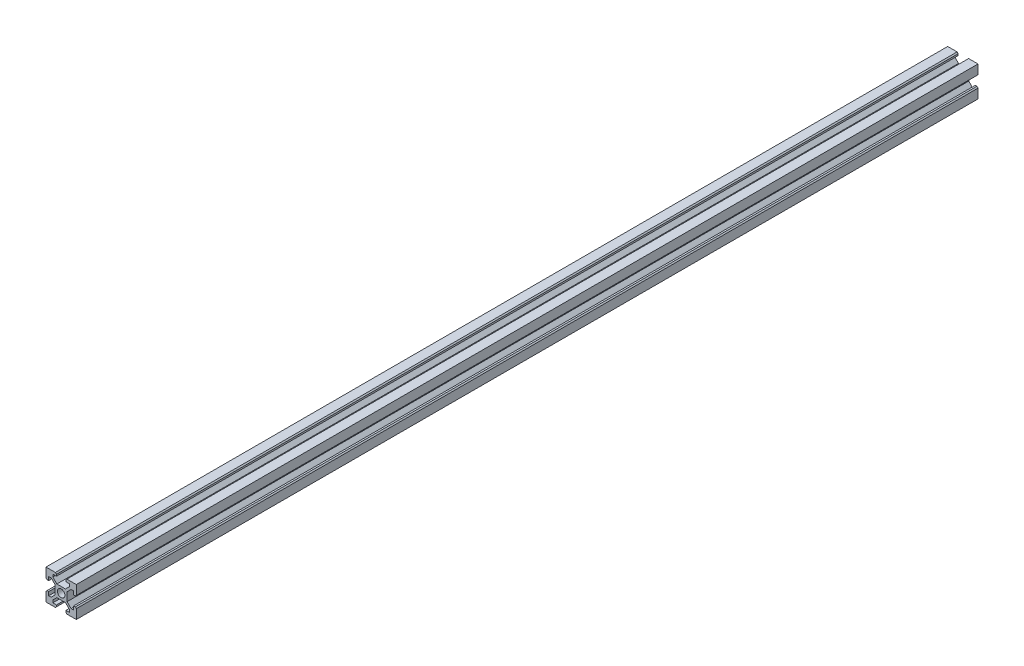
SolidWorks part; units mm, degrees
material "1060 Alloy"
ref_plane "Front Plane" through (0, 0, 0) normal (0, 0, 1) x (1, 0, 0)
ref_plane "Top Plane" through (0, 0, 0) normal (0, 1, 0) x (1, 0, 0)
ref_plane "Right Plane" through (0, 0, 0) normal (1, 0, 0) x (0, 0, -1)
sketch "Sketch1" plane through (0, 0, 0) normal (0, 0, 1) x (1, 0, 0)
  line L0 (3.9, -2.8393) -> (6.5607, -5.5)
  line L1 (-10, 10) -> (10, 10) construction
  line L2 (-10, 10) -> (-10, -10) construction
  line L3 (-10, -10) -> (10, -10) construction
  line L4 (10, 10) -> (10, -10) construction
  line L5 (-10, 10) -> (10, -10) construction
  line L6 (-10, -10) -> (10, 10) construction
  line L7 (-3.9, -3.9) -> (3.9, -3.9) construction
  line L8 (-3.9, -3.9) -> (-3.9, 3.9) construction
  line L9 (-3.9, 3.9) -> (3.9, 3.9) construction
  line L10 (3.9, -3.9) -> (3.9, 3.9) construction
  line L11 (-3.9, -3.9) -> (3.9, 3.9) construction
  line L12 (-3.9, 3.9) -> (3.9, -3.9) construction
  line L13 (-10, 10) -> (-5.5, 10) construction
  line L14 (-10, 10) -> (-10, 5.5) construction
  line L15 (-10, 5.5) -> (-5.5, 5.5) construction
  line L16 (-5.5, 10) -> (-5.5, 5.5) construction
  line L17 (10, 10) -> (5.5, 10) construction
  line L18 (10, 10) -> (10, 5.5) construction
  line L19 (10, 5.5) -> (5.5, 5.5) construction
  line L20 (5.5, 10) -> (5.5, 5.5) construction
  line L21 (-10, -10) -> (-5.5, -10) construction
  line L22 (-10, -10) -> (-10, -5.5) construction
  line L23 (-10, -5.5) -> (-5.5, -5.5) construction
  line L24 (-5.5, -10) -> (-5.5, -5.5) construction
  line L25 (10, -10) -> (5.5, -10) construction
  line L26 (10, -10) -> (10, -5.5) construction
  line L27 (10, -5.5) -> (5.5, -5.5) construction
  line L28 (5.5, -10) -> (5.5, -5.5) construction
  line L29 (2.8393, -3.9) -> (5.5, -6.5607)
  line L30 (-5.5, 6.5607) -> (-2.8393, 3.9)
  line L31 (-6.5607, 5.5) -> (-3.9, 2.8393)
  line L32 (5.5, 6.5607) -> (2.8393, 3.9)
  line L33 (6.5607, 5.5) -> (3.9, 2.8393)
  line L34 (-6.5607, -5.5) -> (-3.9, -2.8393)
  line L35 (-5.5, -6.5607) -> (-2.8393, -3.9)
  line L36 (-2.8393, 3.9) -> (2.8393, 3.9)
  line L37 (-3.9, 2.8393) -> (-3.9, -2.8393)
  line L38 (-2.8393, -3.9) -> (2.8393, -3.9)
  line L39 (3.9, -2.8393) -> (3.9, 2.8393)
  line L40 (5.5, 6.5607) -> (5.5, 8.2007)
  line L41 (5.5, 8.2007) -> (3.1, 8.2007)
  line L42 (3.1, 8.2007) -> (3.1, 9.3)
  line L43 (3.1, 9.3) -> (3.8, 10)
  line L44 (3.8, 10) -> (10, 10)
  line L45 (10, 10) -> (10, 3.8)
  line L46 (10, 3.8) -> (9.3, 3.1)
  line L47 (9.3, 3.1) -> (8.2007, 3.1)
  line L48 (8.2007, 3.1) -> (8.2007, 5.5)
  line L49 (8.2007, 5.5) -> (6.5607, 5.5)
  line L50 (3.1, -8.2007) -> (5.5, -8.2007)
  line L51 (3.1, -9.3) -> (3.1, -8.2007)
  line L52 (3.8, -10) -> (3.1, -9.3)
  line L53 (10, -10) -> (3.8, -10)
  line L54 (10, -3.8) -> (10, -10)
  line L55 (9.3, -3.1) -> (10, -3.8)
  line L56 (8.2007, -3.1) -> (9.3, -3.1)
  line L57 (8.2007, -5.5) -> (8.2007, -3.1)
  line L58 (6.5607, -5.5) -> (8.2007, -5.5)
  line L59 (5.5, -8.2007) -> (5.5, -6.5607)
  line L60 (-8.2007, -3.1) -> (-8.2007, -5.5)
  line L61 (-9.3, -3.1) -> (-8.2007, -3.1)
  line L62 (-10, -3.8) -> (-9.3, -3.1)
  line L63 (-10, -10) -> (-10, -3.8)
  line L64 (-3.8, -10) -> (-10, -10)
  line L65 (-3.1, -9.3) -> (-3.8, -10)
  line L66 (-3.1, -8.2007) -> (-3.1, -9.3)
  line L67 (-5.5, -8.2007) -> (-3.1, -8.2007)
  line L68 (-5.5, -6.5607) -> (-5.5, -8.2007)
  line L69 (-8.2007, -5.5) -> (-6.5607, -5.5)
  line L70 (-3.1, 8.2007) -> (-5.5, 8.2007)
  line L71 (-3.1, 9.3) -> (-3.1, 8.2007)
  line L72 (-3.8, 10) -> (-3.1, 9.3)
  line L73 (-10, 10) -> (-3.8, 10)
  line L74 (-10, 3.8) -> (-10, 10)
  line L75 (-9.3, 3.1) -> (-10, 3.8)
  line L76 (-8.2007, 3.1) -> (-9.3, 3.1)
  line L77 (-8.2007, 5.5) -> (-8.2007, 3.1)
  line L78 (-6.5607, 5.5) -> (-8.2007, 5.5)
  line L79 (-5.5, 8.2007) -> (-5.5, 6.5607)
  circle A0 centre (0, 0) radius 2.5
  point P83 (0, 0)
  dimension "D1" = 5
  dimension "D2" = 20
  dimension "D3" = 7.8
  dimension "D4" = 4.5
  dimension "D5" = 1.5
  dimension "D6" = 0.75
  dimension "D7" = 1.5
  dimension "D8" = 0.75
  dimension "D9" = 1.5
  dimension "D10" = 0.75
  dimension "D11" = 1.5
  dimension "D12" = 0.75
  dimension "D13" = 1.64
  dimension "D14" = 45
  dimension "D15" = 3.1
  dimension "D16" = 6.2
  dimension "D17" = 6.2
  dimension "D18" = 3.1
  dimension "D19" = 4
extrude "Boss-Extrude1" add sketch "Sketch1" along normal mid plane 595 contours L79 L70 L71 L72 L73 L74 L75 L76 L77 L78 L31 L37 L34 L69 L60 L61 L62 L63 L64 L65 L66 L67 L68 L35 L38 L29 L59 L50 L51 L52 L53 L54 L55 L56 L57 L58 L0 L39 L33 L49 L48 L47 L46 L45 L44 L43 L42 L41 L40 L32 L36
